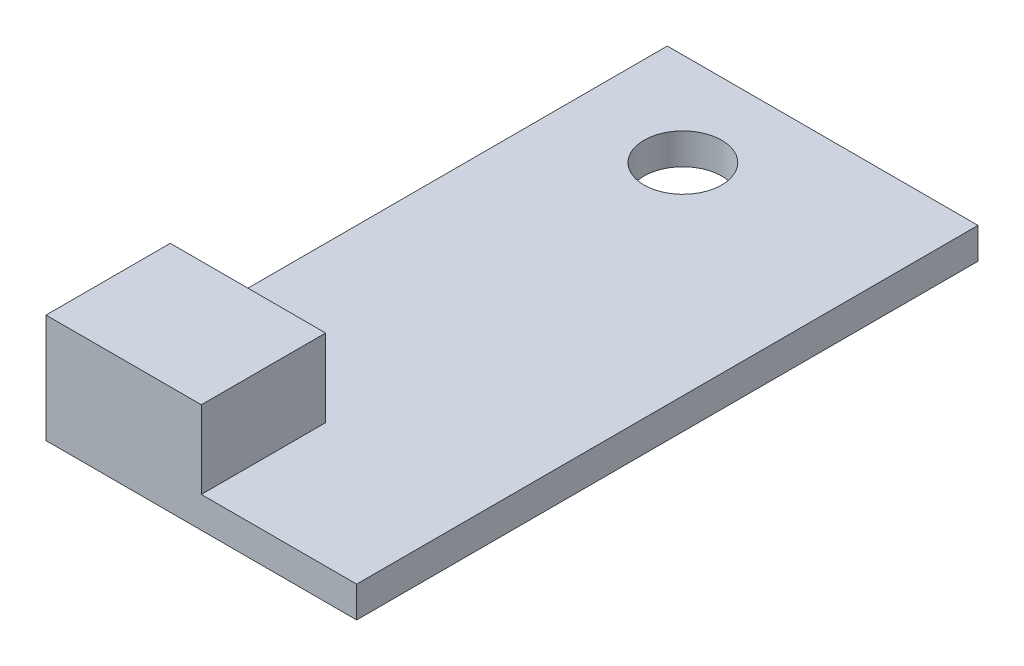
SolidWorks part; units mm, degrees
ref_plane "Front Plane" through (0, 0, 0) normal (0, 0, 1) x (1, 0, 0)
ref_plane "Top Plane" through (0, 0, 0) normal (0, 1, 0) x (1, 0, 0)
ref_plane "Right Plane" through (0, 0, 0) normal (1, 0, 0) x (0, 0, -1)
sketch "Sketch1" plane through (0, 0, 0) normal (0, 1, 0) x (1, 0, 0)
  line L1 (0, 0) -> (100, 0)
  line L2 (0, 0) -> (0, 200)
  line L3 (0, 200) -> (100, 200)
  line L4 (100, 0) -> (100, 200)
  dimension "D1" = 100
  dimension "D2" = 200
extrude "Boss-Extrude1" add sketch "Sketch1" along normal blind 10
sketch "Sketch2" plane through (0, 10, 0) normal (0, 1, 0) x (1, 0, 0)
  line L1 (0, 0) -> (50, 0)
  line L2 (0, 0) -> (0, 40)
  line L3 (0, 40) -> (50, 40)
  line L4 (50, 0) -> (50, 40)
  dimension "D1" = 40
  dimension "D2" = 50
extrude "Boss-Extrude2" add sketch "Sketch2" along normal blind 25
hole_wizard "Ø25.0 (25) Diameter Hole1" positions "Sketch3" profile "Sketch4" hole size "Ø25.0" standard "ANSI Metric" end condition through all
sketch "Sketch3" plane through (0, 10, 0) normal (0, 1, 0) x (1, 0, 0)
  line L0 (0, 200) -> (0, 40) construction
  line L1 (100, 200) -> (0, 200) construction
  point P0 (35, 170)
  dimension "D1" = 35
  dimension "D2" = 30
sketch "Sketch4" plane through (35, 10, -170) normal (1, 0, 0) x (0, 0, 1)
  line L0 (0, 0) -> (0, 10)
  line L1 (0, 10) -> (12.5, 10)
  line L2 (12.5, 10) -> (12.5, 0)
  line L5 (12.5, 0) -> (0, 0)
  line L11 (0, -6.35) -> (0, 107.95) construction
  dimension "Thru Hole Dia." = 25
  dimension "Thru Hole Depth" = 10
